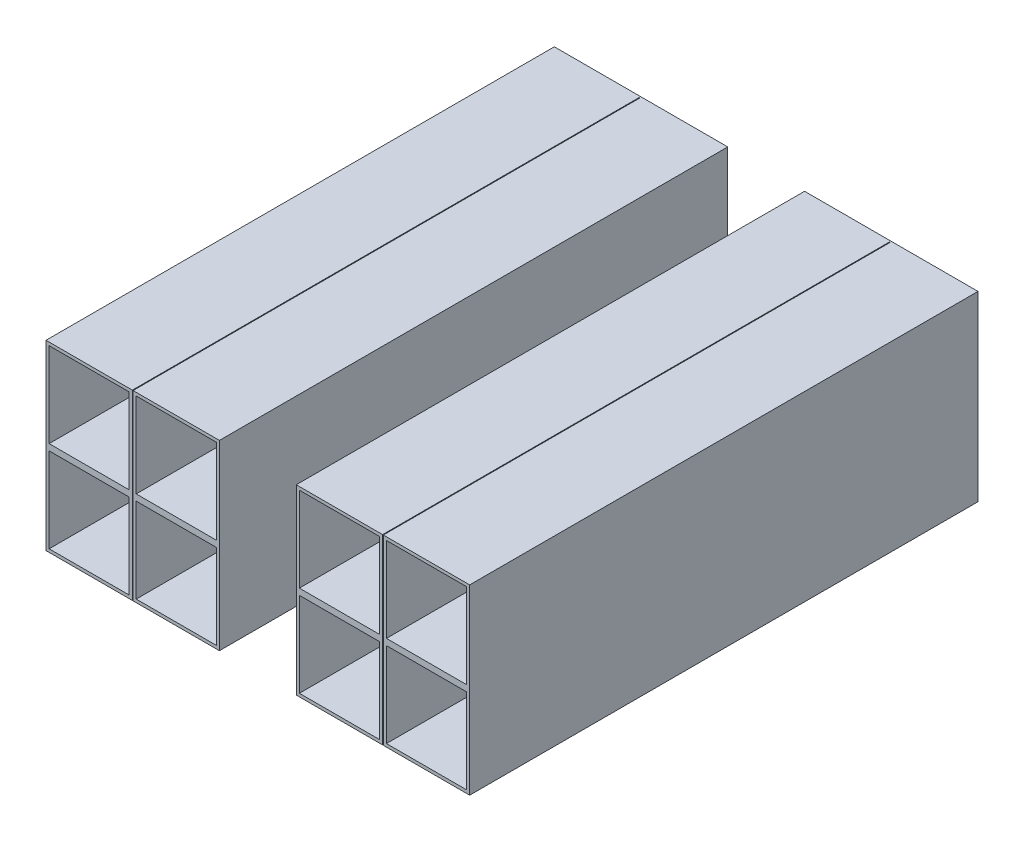
SolidWorks part; units mm, degrees
ref_plane "Front Plane" through (0, 0, 0) normal (0, 0, 1) x (1, 0, 0)
ref_plane "Top Plane" through (0, 0, 0) normal (0, 1, 0) x (1, 0, 0)
ref_plane "Right Plane" through (0, 0, 0) normal (1, 0, 0) x (0, 0, -1)
sketch "Sketch1" plane through (0, 0, 0) normal (0, 0, 1) x (1, 0, 0)
  line L0 (200, 147.6604) -> (200, -167.6318) construction
  line L9 (61.4, 145.588) -> (199.4, 145.588)
  line L22 (61.4, 145.588) -> (61.4, -145.588)
  line L25 (61.4, -145.588) -> (199.4, -145.588)
  line L28 (199.4, 145.588) -> (199.4, -145.588)
  line L30 (66.4, 140.588) -> (194.4, 140.588)
  line L31 (66.4, 140.588) -> (66.4, 5)
  line L32 (66.4, 5) -> (194.4, 5)
  line L33 (194.4, 140.588) -> (194.4, 5)
  line L34 (66.4, -5) -> (194.4, -5)
  line L35 (66.4, -5) -> (66.4, -140.588)
  line L36 (66.4, -140.588) -> (194.4, -140.588)
  line L37 (194.4, -5) -> (194.4, -140.588)
  line L38 (338.6, -145.588) -> (200.6, -145.588)
  line L39 (200.6, 145.588) -> (200.6, -145.588)
  line L40 (338.6, 145.588) -> (200.6, 145.588)
  line L41 (338.6, 145.588) -> (338.6, -145.588)
  line L42 (333.6, -140.588) -> (205.6, -140.588)
  line L43 (205.6, -5) -> (205.6, -140.588)
  line L44 (333.6, -5) -> (205.6, -5)
  line L45 (333.6, -5) -> (333.6, -140.588)
  line L46 (333.6, 5) -> (205.6, 5)
  line L47 (205.6, 140.588) -> (205.6, 5)
  line L48 (333.6, 140.588) -> (205.6, 140.588)
  line L49 (333.6, 140.588) -> (333.6, 5)
  line L50 (0, 73.4075) -> (0, -79.5851) construction
  line L51 (61.4, 0) -> (338.6, 0) construction
  line L52 (-338.6, 145.588) -> (-338.6, -145.588)
  line L53 (-338.6, 145.588) -> (-200.6, 145.588)
  line L54 (-200.6, 145.588) -> (-200.6, -145.588)
  line L55 (-338.6, -145.588) -> (-200.6, -145.588)
  line L56 (-61.4, -145.588) -> (-199.4, -145.588)
  line L57 (-199.4, 145.588) -> (-199.4, -145.588)
  line L58 (-61.4, 145.588) -> (-199.4, 145.588)
  line L59 (-61.4, 145.588) -> (-61.4, -145.588)
  line L60 (-66.4, -140.588) -> (-194.4, -140.588)
  line L61 (-194.4, -5) -> (-194.4, -140.588)
  line L62 (-66.4, -5) -> (-194.4, -5)
  line L63 (-66.4, -5) -> (-66.4, -140.588)
  line L64 (-333.6, -5) -> (-333.6, -140.588)
  line L65 (-333.6, -5) -> (-205.6, -5)
  line L66 (-205.6, -5) -> (-205.6, -140.588)
  line L67 (-333.6, -140.588) -> (-205.6, -140.588)
  line L68 (-333.6, 140.588) -> (-333.6, 5)
  line L69 (-333.6, 140.588) -> (-205.6, 140.588)
  line L70 (-205.6, 140.588) -> (-205.6, 5)
  line L71 (-333.6, 5) -> (-205.6, 5)
  line L72 (-66.4, 5) -> (-194.4, 5)
  line L73 (-194.4, 140.588) -> (-194.4, 5)
  line L74 (-66.4, 140.588) -> (-194.4, 140.588)
  line L75 (-66.4, 140.588) -> (-66.4, 5)
  line L76 (269.6, 140.588) -> (269.6, 5) construction
  line L77 (130.4, 140.588) -> (130.4, 5) construction
  line L78 (-199.4, 145.588) -> (-200, 145.588) construction
  line L79 (-200, 145.588) -> (-200, -145.588) construction
  line L80 (-200.6, 145.588) -> (-200, 145.588) construction
  line L81 (66.4, 72.794) -> (194.4, 72.794) construction
  line L82 (66.4, -72.794) -> (194.4, -72.794) construction
  dimension "D2" = 145.588
  dimension "D3" = 5
  dimension "D4" = 5
  dimension "D5" = 10
  dimension "D1" = 138
  dimension "D6" = 5
  dimension "D7" = 5
  dimension "D8" = 139.2
  dimension "D9" = 400
extrude "Boss-Extrude1" add sketch "Sketch1" along normal mid plane 810
sketch "Sketch2" plane through (0, 0, -405) normal (0, 0, -1) x (-1, 0, 0)
  line L5 (-338.6, 145.588) -> (-61.4, 145.588)
  line L6 (-338.6, 145.588) -> (-338.6, -145.588)
  line L7 (-338.6, -145.588) -> (-61.4, -145.588)
  line L8 (-61.4, 145.588) -> (-61.4, -145.588)
  line L9 (61.4, 145.588) -> (338.6, 145.588)
  line L10 (61.4, 145.588) -> (61.4, -145.588)
  line L11 (61.4, -145.588) -> (338.6, -145.588)
  line L12 (338.6, 145.588) -> (338.6, -145.588)
extrude "Boss-Extrude2" add sketch "Sketch2" along normal blind 2.5
